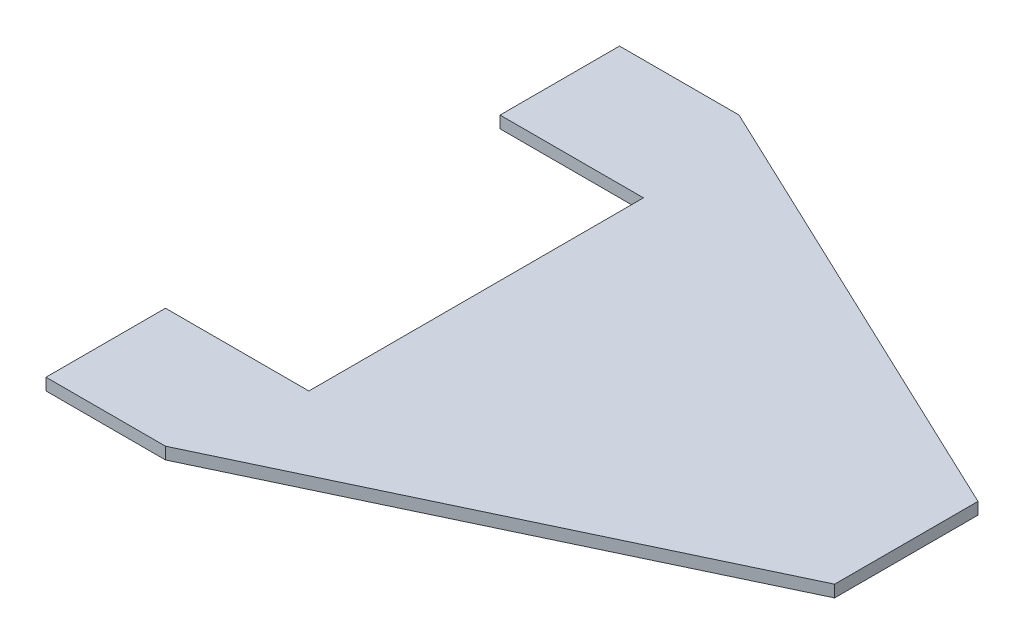
SolidWorks part; units mm, degrees
ref_plane "Front" through (0, 0, 0) normal (0, 0, 1) x (1, 0, 0)
ref_plane "Top" through (0, 0, 0) normal (0, 1, 0) x (1, 0, 0)
ref_plane "Right" through (0, 0, 0) normal (1, 0, 0) x (0, 0, -1)
sketch "Sketch1" plane through (0, 0, 0) normal (0, 1, 0) x (1, 0, 0)
  line L2 (76.2, 88.9) -> (76.2, -88.9)
  line L3 (76.2, -88.9) -> (0, -88.9)
  line L4 (0, -88.9) -> (0, -152.4)
  line L5 (0, -152.4) -> (63.5, -152.4)
  line L6 (63.5, -152.4) -> (304.8, -38.1)
  line L7 (304.8, -38.1) -> (304.8, 38.1)
  line L10 (0, 0) -> (304.8, 0) construction
  line L11 (63.5, 152.4) -> (304.8, 38.1)
  line L12 (0, 152.4) -> (63.5, 152.4)
  line L13 (0, 88.9) -> (0, 152.4)
  line L14 (76.2, 88.9) -> (0, 88.9)
  point P1 (0, 0)
  point P9 (304.8, 0)
  point P15 (76.2, 0)
  point P16 (155.523, 38.1)
  point P17 (0, 0)
  point P18 (0, 0)
  point P19 (0, 0)
  point P20 (0, 0)
  dimension "D1" = 63.5
  dimension "D2" = 304.8
  dimension "D3" = 63.5
  dimension "D4" = 76.2
  dimension "D5" = 76.2
  dimension "D6" = 304.8
extrude "Boss-Extrude1" add sketch "Sketch1" along normal blind 6.35
